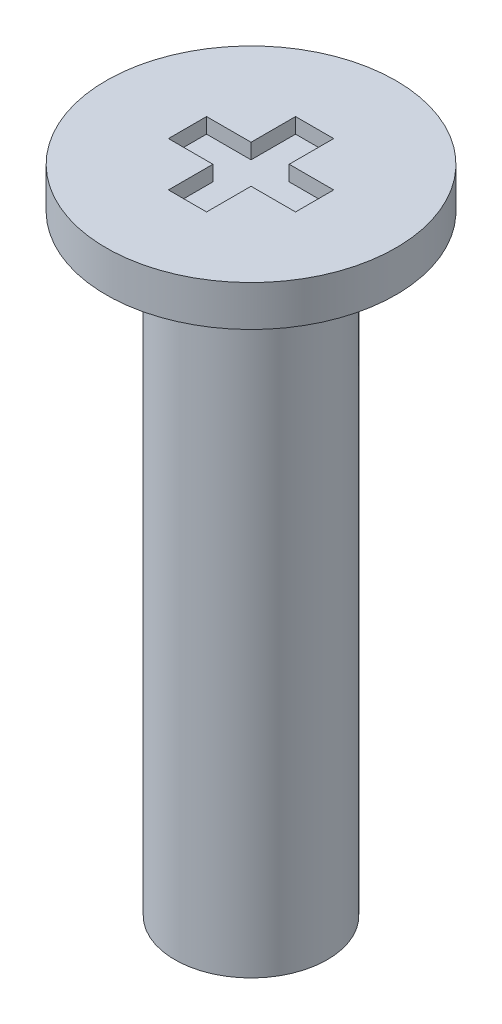
SolidWorks part; units mm, degrees
material "S45C"
ref_plane "正面" through (0, 0, 0) normal (0, 0, 1) x (1, 0, 0)
ref_plane "平面" through (0, 0, 0) normal (0, 1, 0) x (1, 0, 0)
ref_plane "右側面" through (0, 0, 0) normal (1, 0, 0) x (0, 0, -1)
sketch "ｽｹｯﾁ1" plane through (0, 0, 0) normal (0, 0, 1) x (1, 0, 0)
  line L0 (0, 0) -> (2.85, 0)
  line L1 (2.85, 0) -> (2.85, -0.8)
  line L2 (2.85, -0.8) -> (1.5, -0.8)
  line L3 (1.5, -0.8) -> (1.5, -12.8)
  line L4 (1.5, -12.8) -> (0, -12.8)
  line L5 (0, -12.8) -> (0, 0)
  dimension "D1" = 2.85
  dimension "D2" = 0.8
  dimension "D3" = 1.5
  dimension "D4" = 12
revolve "回転1" add sketch "ｽｹｯﾁ1" angle 360 about L5
sketch "ｽｹｯﾁ2" plane through (0, 0, 0) normal (0, 1, 0) x (1, 0, 0)
  line L1 (-0.375, 0) -> (0.375, 0)
  line L2 (-0.375, 0) -> (-0.375, 1.25)
  line L3 (-0.375, 1.25) -> (0.375, 1.25)
  line L4 (0.375, 0) -> (0.375, 1.25)
  line L5 (-0.375, 0) -> (0.375, 1.25) construction
  line L6 (-0.375, 1.25) -> (0.375, 0) construction
  point P4 (0, 0.625)
  dimension "D1" = 0
  dimension "D2" = 0.75
  dimension "D3" = 1.25
  dimension "D4" = 0
extrude "ｶｯﾄ - 押し出し1" cut sketch "ｽｹｯﾁ2" against normal blind 0.3
pattern_circular "円形ﾊﾟﾀｰﾝ1" count 4 over 360 about axis through (0, 0, 0) along (0, 1, 0) of "ｶｯﾄ - 押し出し1"
